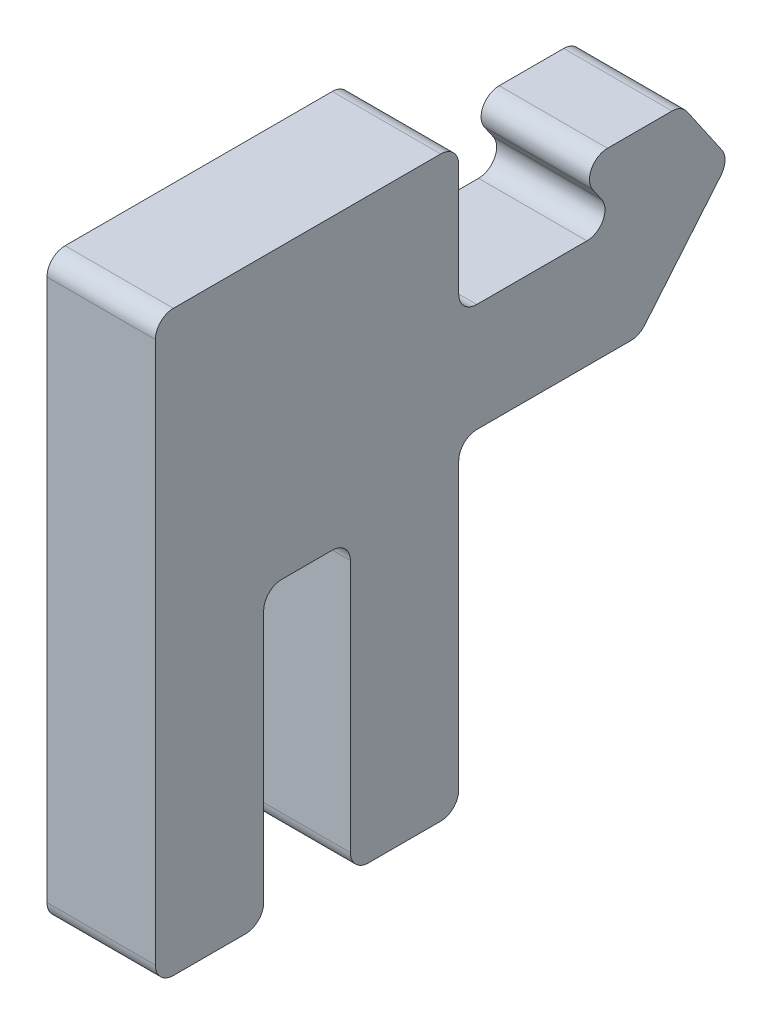
SolidWorks part; units mm, degrees
ref_plane "Alzado" through (0, 0, 0) normal (0, 0, 1) x (1, 0, 0)
ref_plane "Planta" through (0, 0, 0) normal (0, 1, 0) x (1, 0, 0)
ref_plane "Vista lateral" through (0, 0, 0) normal (1, 0, 0) x (0, 0, -1)
sketch "Croquis1" plane through (0, 0, 0) normal (1, 0, 0) x (0, 0, -1)
  line L1 (-4.2, 8) -> (4.2, 8)
  line L2 (-4.2, 8) -> (-4.2, -8)
  line L3 (-4.2, -8) -> (4.2, -8)
  line L16 (4.2, 8) -> (4.2, -8)
  dimension "D1" = 4.2
  dimension "D2" = 8
  dimension "D3" = 16
  dimension "D4" = 8.4
extrude "Saliente-Extruir1" add sketch "Croquis1" along normal blind 3
sketch "Croquis2" plane through (3, 0, 0) normal (1, 0, 0) x (0, 0, -1)
  line L0 (0, 0) -> (0, -9.3656) construction
  line L1 (-4.2, -8) -> (4.2, -8) construction
  line L2 (-1.2, -8) -> (1.2, -8)
  line L3 (-1.2, -8) -> (-1.2, 0)
  line L4 (-1.2, 0) -> (1.2, 0)
  line L5 (1.2, -8) -> (1.2, 0)
  dimension "D1" = 1.2
  dimension "D2" = 1.2
  dimension "D3" = 8
extrude "Cortar-Extruir1" cut sketch "Croquis2" against normal up to surface (3 mm away) up to face at (0, 0, 0)
sketch "Croquis4" plane through (3, 0, 0) normal (1, 0, 0) x (0, 0, -1)
  line L9 (1.2, 0) -> (-1.2, 0) construction
  line L10 (0, 0) -> (0, 10.8389) construction
  line L18 (4.2, 3.8918) -> (4.2, 0.8918)
  line L19 (4.2, -8) -> (4.2, 8) construction
  line L20 (4.2, 0.8918) -> (9.2, 0.8918)
  line L22 (8.7, 3.8918) -> (4.2, 3.8918)
  line L25 (7.3691, 5.8274) -> (8.7, 3.8918)
  line L26 (7.3691, 5.8274) -> (10.3691, 5.8274)
  line L27 (10.3691, 5.8274) -> (11.6997, 3.8922)
  line L28 (11.6997, 3.8922) -> (9.2, 0.8918)
  point P6 (11.8287, 3.7046)
  point P14 (11.6997, 3.8918)
  dimension "D1" = 5
  dimension "D2" = 3
  dimension "D3" = 4.5
  dimension "D4" = 3.8918
  dimension "D5" = 5.8274
  dimension "D6" = 2.9997
  dimension "D7" = 3
  dimension "D8" = 11.8459
extrude "Saliente-Extruir2" add sketch "Croquis4" against normal up to surface (3 mm away) up to face at (0, -2, 0)
fillet "Redondeo1" radius 0.5 15 edges at (1.5, 8, 4.2) (1.5, 3.8918, -4.2) (1.5, 8, -4.2) (1.5, 5.8274, -7.3691) (1.5, 5.8274, -10.3691) (1.5, 3.8922, -11.6997) (1.5, 0.8918, -9.2) (1.5, 0.8918, -4.2) (1.5, 0, -1.2) (1.5, 0, 1.2) (1.5, -8, 1.2) (1.5, -8, 4.2) (1.5, -8, -4.2) (1.5, -8, -1.2) (1.5, 3.8918, -8.7)
